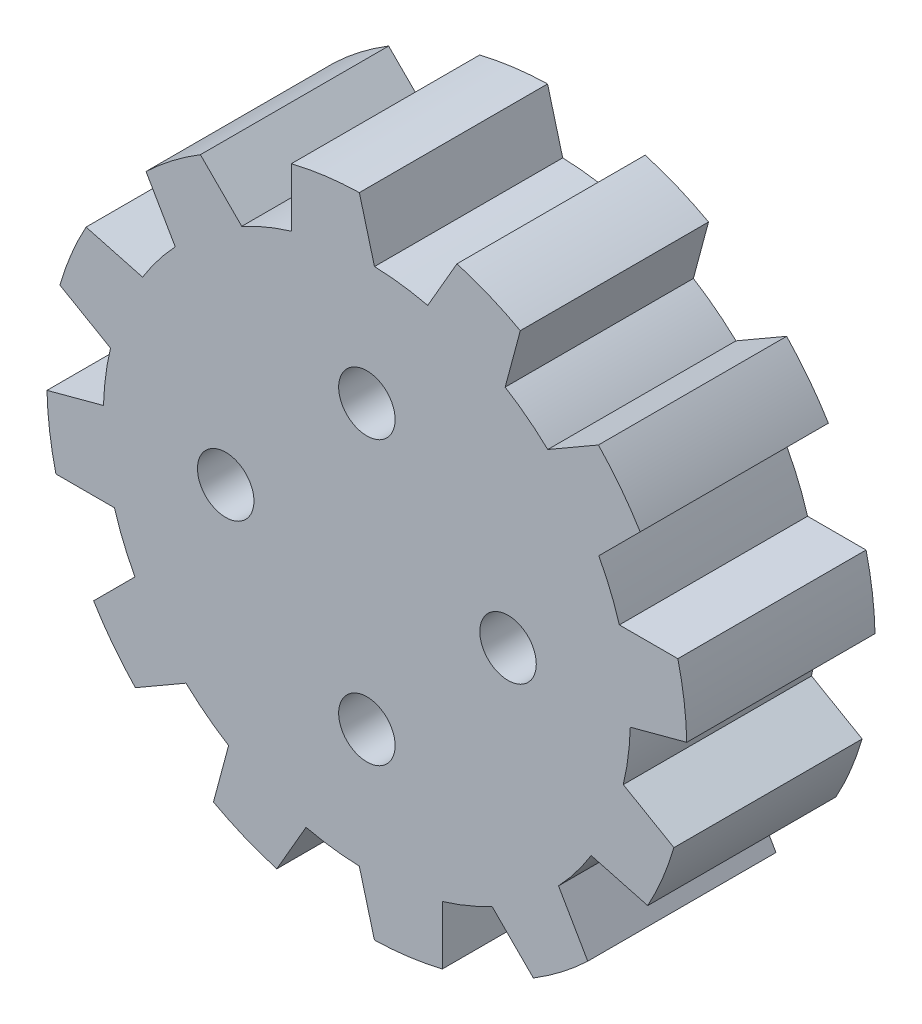
SolidWorks part; units mm, degrees
material "ABS"
ref_plane "前基準面" through (0, 0, 0) normal (0, 0, 1) x (1, 0, 0)
ref_plane "上基準面" through (0, 0, 0) normal (0, 1, 0) x (1, 0, 0)
ref_plane "右基準面" through (0, 0, 0) normal (1, 0, 0) x (0, 0, -1)
sketch "草圖1" plane through (0, 0, 0) normal (0, 0, 1) x (1, 0, 0)
  line L0 (-11.9176, 7.3465) -> (-14.9187, 8.1507)
  line L1 (-11.7342, 12.3008) -> (-10.1807, 9.6101)
  line L2 (-6.6477, 12.3211) -> (-8.8446, 14.518)
  line L3 (-4.0117, 16.5199) -> (-4.0117, 13.4129)
  line L4 (0.4035, 13.9942) -> (-0.4007, 16.9953)
  line L5 (4.7857, 16.3125) -> (3.2322, 13.6218)
  line L6 (7.3465, 11.9176) -> (8.1507, 14.9187)
  line L7 (12.3008, 11.7342) -> (9.6101, 10.1807)
  line L8 (12.3211, 6.6477) -> (14.518, 8.8446)
  line L9 (16.5199, 4.0117) -> (13.4129, 4.0117)
  line L10 (13.9942, -0.4035) -> (16.9953, 0.4007)
  line L11 (16.3125, -4.7857) -> (13.6218, -3.2322)
  line L12 (11.9176, -7.3465) -> (14.9187, -8.1507)
  line L13 (11.7342, -12.3008) -> (10.1807, -9.6101)
  line L14 (6.6477, -12.3211) -> (8.8446, -14.518)
  line L15 (4.0117, -16.5199) -> (4.0117, -13.4129)
  line L16 (-0.4035, -13.9942) -> (0.4007, -16.9953)
  line L17 (-4.7857, -16.3125) -> (-3.2322, -13.6218)
  line L18 (-7.3465, -11.9176) -> (-8.1507, -14.9187)
  line L19 (-12.3008, -11.7342) -> (-9.6101, -10.1807)
  line L20 (-12.3211, -6.6477) -> (-14.518, -8.8446)
  line L21 (-16.5199, -4.0117) -> (-13.4129, -4.0117)
  line L25 (-13.9942, 0.4035) -> (-16.9953, -0.4007)
  line L26 (-16.3125, 4.7857) -> (-13.6218, 3.2322)
  circle A0 centre (0, 0) radius 17
  circle A1 centre (0, 0) radius 14
  dimension "D1" = 34
  dimension "D2" = 12
  dimension "D3" = 28
extrude "填料-伸長2" add sketch "草圖1" along normal blind 10 contours A1 | A1 L4 A0 L3 | A1 L6 A0 L5 | A1 L8 A0 L7 | A1 L10 A0 L9 | A1 L12 A0 L11 | A1 L14 A0 L13 | A1 L16 A0 L15 | A1 L18 A0 L17 | A1 L20 A0 L19 | A1 L25 A0 L21 | A1 L0 A0 L26 | A1 L2 A0 L1
sketch "草圖2" plane through (0, 0, 0) normal (0, 0, -1) x (-1, 0, 0)
  circle A0 centre (0, 0) radius 10.75
  dimension "D1" = 21.5
extrude "除料-伸長1" cut sketch "草圖2" against normal blind 4
sketch "草圖3" plane through (0, 0, 10) normal (0, 0, 1) x (1, 0, 0)
  circle A0 centre (-7.5, 0) radius 1.5
  circle A1 centre (7.5, 0) radius 1.5
  circle A2 centre (0, 7.5) radius 1.5
  circle A3 centre (0, -7.5) radius 1.5
  dimension "D5" = 3
  dimension "D6" = 3
  dimension "D7" = 3
  dimension "D8" = 3
  dimension "D1" = 7.5
  dimension "D2" = 7.5
  dimension "D3" = 7.5
  dimension "D4" = 7.5
extrude "除料-伸長2" cut sketch "草圖3" against normal blind 10
sketch "草圖4" plane through (0, 0, 4) normal (0, 0, -1) x (-1, 0, 0)
  circle A0 centre (0, 0) radius 3.75
  dimension "D1" = 7.5
extrude "除料-伸長3" cut sketch "草圖4" against normal blind 1
